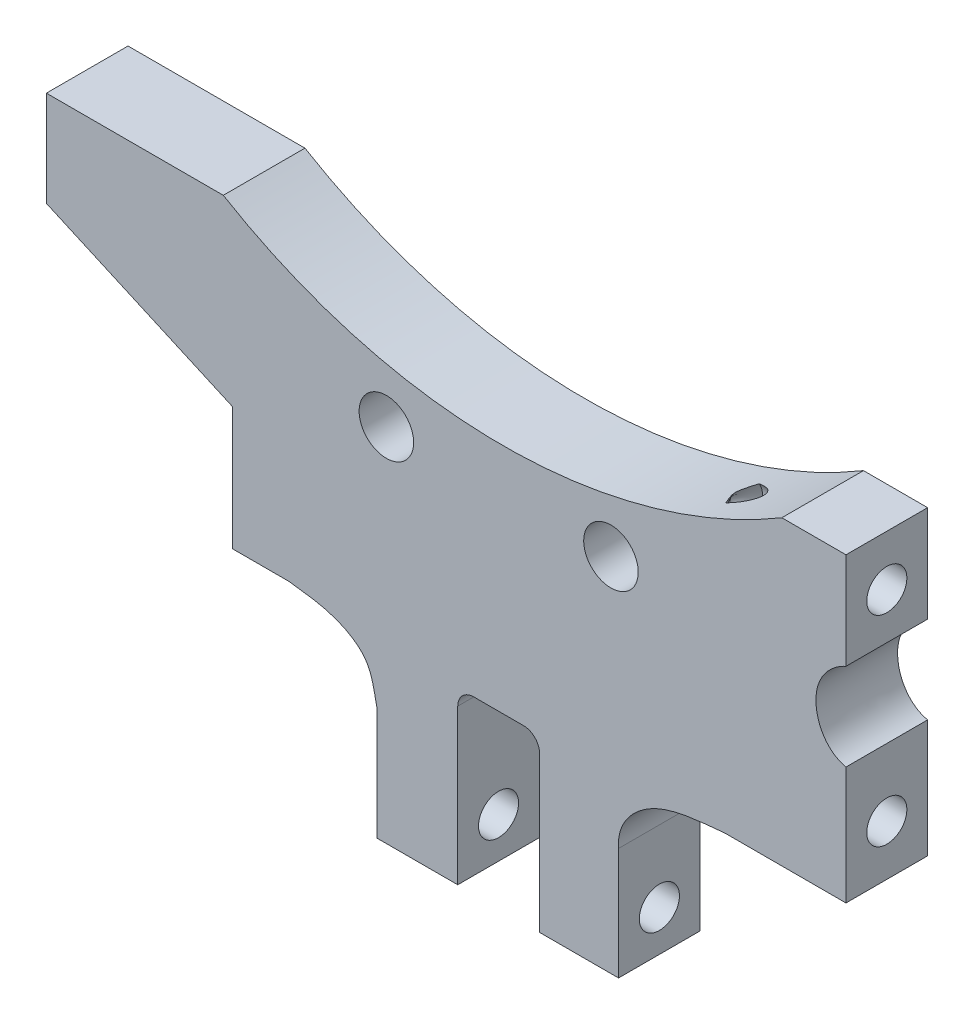
SolidWorks part; units mm, degrees
ref_plane "Piano frontale" through (0, 0, 0) normal (0, 0, 1) x (1, 0, 0)
ref_plane "Piano superiore" through (0, 0, 0) normal (0, 1, 0) x (1, 0, 0)
ref_plane "Piano destro" through (0, 0, 0) normal (1, 0, 0) x (0, 0, -1)
sketch "Schizzo2" plane through (0, 0, 0) normal (0, 0, 1) x (1, 0, 0)
  line L0 (13.4087, 34.0468) -> (25.0087, 28.8748)
  line L1 (25.0087, 28.8748) -> (25.0087, 21.1979)
  line L2 (25.0087, 21.1979) -> (28.5396, 21.1979)
  line L3 (63.2587, 21.1979) -> (55.7174, 21.1979)
  line L4 (63.2587, 21.1979) -> (63.2587, 28.54)
  line L5 (34.0312, 10.0791) -> (39.0542, 10.0791)
  line L6 (39.0542, 10.0791) -> (39.0542, 19.7231)
  line L7 (40.0542, 20.7231) -> (43.1569, 20.7231)
  line L8 (44.1569, 19.7231) -> (44.1569, 10.0592)
  line L9 (44.1569, 10.0592) -> (49.0802, 10.0592)
  line L10 (49.0802, 10.0592) -> (49.0802, 17.0555)
  line L11 (34.0312, 10.0791) -> (34.0312, 17.0555)
  line L12 (63.2587, 33.9782) -> (63.2587, 39.9979)
  line L13 (13.4087, 34.0468) -> (13.4087, 39.9979)
  line L14 (63.2587, 39.9979) -> (59.2587, 39.9979)
  line L15 (24.4387, 39.9979) -> (13.4087, 39.9979)
  arc A0 (43.1569, 20.7231) -> (44.1569, 19.7231) centre (43.1569, 19.7231) cw
  arc A1 (39.0542, 19.7231) -> (40.0542, 20.7231) centre (40.0542, 19.7231) cw
  arc A2 (24.4387, 39.9979) -> (59.2587, 39.9979) centre (41.8487, 69.1717) ccw
  spline S0 degree 3 poles (28.5396, 21.1979) (29.6727, 21.0547) (31.4423, 20.8837) (33.71, 19.3379) (33.8602, 17.78) (34.0312, 17.0555) knots 0 0 0 0 0.446669 0.694826 1 1 1 1
  spline S1 degree 3 poles (49.0802, 17.0555) (48.9673, 18.3463) (50.9996, 20.921) (54.1131, 21.0356) (55.7174, 21.1979) knots 0 0 0 0 0.423714 1 1 1 1
  spline S2 degree 3 poles (63.2587, 28.54) (62.2397, 28.7594) (61.2539, 30.1822) (61.4488, 32.6296) (62.5365, 33.6541) (63.2587, 33.9782) knots 0 0 0 0 0.415878 0.656562 1 1 1 1
  point P36 (41.8487, 35.1979)
  dimension "D1" = 1
  dimension "D2" = 4
  dimension "D3" = 18.8
  dimension "D4" = 4.8
  dimension "D5" = 38.25
  dimension "D6" = 11.6
extrude "Estrusione-Estrusione1" add sketch "Schizzo2" along normal blind 5.09
hole_wizard "Foro svasato per Vite M3-1" positions "Schizzo4" profile "Schizzo3" countersink size "M3" standard "Ansi Metric" end condition through all
sketch "Schizzo4" plane through (0, 0, 0) normal (0, 0, -1) x (-1, 0, 0)
  line L0 (-48.6055, 32.5791) -> (-34.6055, 32.5791) construction
  line L1 (-34.0312, 10.0791) -> (-39.0542, 10.0791) construction
  line L2 (-41.6055, 32.5791) -> (-41.6055, 20.7231) construction
  line L3 (-40.0542, 20.7231) -> (-43.1569, 20.7231) construction
  point P0 (-48.6055, 32.5791)
  point P2 (-34.6055, 32.5791)
  dimension "D1" = 14
  dimension "D2" = 22.5
sketch "Schizzo3" plane through (48.6055, 32.5791, 0) normal (1, 0, 0) x (0, 1, 0)
  line L0 (0, 0) -> (0, 5.09)
  line L1 (0, 5.09) -> (1.7, 5.09)
  line L2 (1.7, 5.09) -> (1.7, 1.45)
  line L3 (1.7, 1.45) -> (3.15, 0)
  line L5 (3.15, 0) -> (0, 0)
  line L6 (-1.7, 1.45) -> (-3.15, 0) construction
  line L11 (0, -6.35) -> (0, 107.95) construction
  dimension "Thru Hole Dia." = 3.4
  dimension "Thru Hole Depth" = 5.09
  dimension "Near C'Sink Dia." = 6.3
  dimension "Near C'Sink Angle" = 90
hole_wizard "Foro filettato M3x0.5-1" positions "Schizzo6" profile "Schizzo5" tap size "M3x0.5" standard "Ansi Metric"
sketch "Schizzo6" plane through (63.2587, 0, 0) normal (1, 0, 0) x (0, 0, -1)
  line L0 (-2.545, 36.8479) -> (-2.545, 24.3479) construction
  line L3 (-5.09, 21.1979) -> (0, 21.1979) construction
  line L4 (0, 39.9979) -> (-5.09, 21.1979) construction
  point P0 (-2.545, 36.8479)
  point P2 (-2.545, 24.3479)
  point P18 (-2.545, 21.1979)
  point P25 (-2.545, 30.5979)
  dimension "D1" = 12.5
sketch "Schizzo5" plane through (63.2587, 36.8479, 2.545) normal (0, 1, 0) x (0, 0, -1)
  line L0 (0, 0) -> (0, 9.7511)
  line L1 (0, 9.7511) -> (1.25, 9)
  line L2 (1.25, 9) -> (1.25, 0)
  line L5 (1.25, 0) -> (0, 0)
  line L10 (0, 9.7511) -> (-1.25, 9) construction
  line L11 (0, -6.35) -> (0, 107.95) construction
  dimension "Tap Drill Dia." = 2.5
  dimension "Tap Drill Depth" = 9
  dimension "Drill Angle" = 118
cosmetic thread "Filettatura del foro1" parameters "D1"=9, "D2"=3
cosmetic thread "Filettatura del foro2" parameters "D1"=9, "D2"=3
hole_wizard "Foro filettato M3x0.5-2" positions "Schizzo8" profile "Schizzo7" tap size "M3x0.5" standard "Ansi Metric"
sketch "Schizzo8" plane through (13.4087, 0, 0) normal (-1, 0, 0) x (0, 0, 1)
  arc A0 (3.5822, 37.5456) -> (1.5078, 37.5456) centre (2.545, 36.8479) ccw construction
  point P0 (2.545, 36.8479)
sketch "Schizzo7" plane through (13.4087, 36.8479, 2.545) normal (0, 1, 0) x (0, 0, 1)
  line L0 (0, 0) -> (0, 9.7511)
  line L1 (0, 9.7511) -> (1.25, 9)
  line L2 (1.25, 9) -> (1.25, 0)
  line L5 (1.25, 0) -> (0, 0)
  line L10 (0, 9.7511) -> (-1.25, 9) construction
  line L11 (0, -6.35) -> (0, 107.95) construction
  dimension "Tap Drill Dia." = 2.5
  dimension "Tap Drill Depth" = 9
  dimension "Drill Angle" = 118
cosmetic thread "Filettatura del foro3" parameters "D1"=9, "D2"=3
hole_wizard "Foro filettato M3x0.5-3" positions "Schizzo10" profile "Schizzo9" tap size "M3x0.5" standard "Ansi Metric"
sketch "Schizzo10" plane through (25.0087, 0, 0) normal (-1, 0, 0) x (0, 0, 1)
  circle A0 centre (2.545, 24.3479) radius 1.25 construction
  point P0 (2.545, 24.3479)
sketch "Schizzo9" plane through (25.0087, 24.3479, 2.545) normal (0, 1, 0) x (0, 0, 1)
  line L0 (0, 0) -> (0, 9.7511)
  line L1 (0, 9.7511) -> (1.25, 9)
  line L2 (1.25, 9) -> (1.25, 0)
  line L5 (1.25, 0) -> (0, 0)
  line L10 (0, 9.7511) -> (-1.25, 9) construction
  line L11 (0, -6.35) -> (0, 107.95) construction
  dimension "Tap Drill Dia." = 2.5
  dimension "Tap Drill Depth" = 9
  dimension "Drill Angle" = 118
cosmetic thread "Filettatura del foro4" parameters "D1"=9, "D2"=3
hole_wizard "Foro filettato M3x0.5-4" positions "Schizzo12" profile "Schizzo11" tap size "M3x0.5" standard "Ansi Metric" end condition through all
sketch "Schizzo12" plane through (49.0802, 0, 0) normal (1, 0, 0) x (0, 0, -1)
  line L0 (-5.09, 10.0592) -> (0, 10.0592) construction
  line L1 (-5.09, 10.0592) -> (-2.545, 12.6042) construction
  line L2 (-5.09, 10.0592) -> (-5.09, 17.0555) construction
  point P0 (-2.545, 12.6042)
  point P5 (-2.545, 10.0592)
  dimension "D1" = 45
sketch "Schizzo11" plane through (49.0802, 12.6042, 2.545) normal (0, 1, 0) x (0, 0, -1)
  line L0 (0, 0) -> (0, 35.6716)
  line L1 (0, 35.6716) -> (1.25, 35.6716)
  line L2 (1.25, 35.6716) -> (1.25, 0)
  line L5 (1.25, 0) -> (0, 0)
  line L11 (0, -6.35) -> (0, 107.95) construction
  dimension "Thru Tap Drill Dia." = 2.5
  dimension "Thru Tap Drill Depth" = 35.6716
cosmetic thread "Filettatura del foro5" parameters "D2"=3
